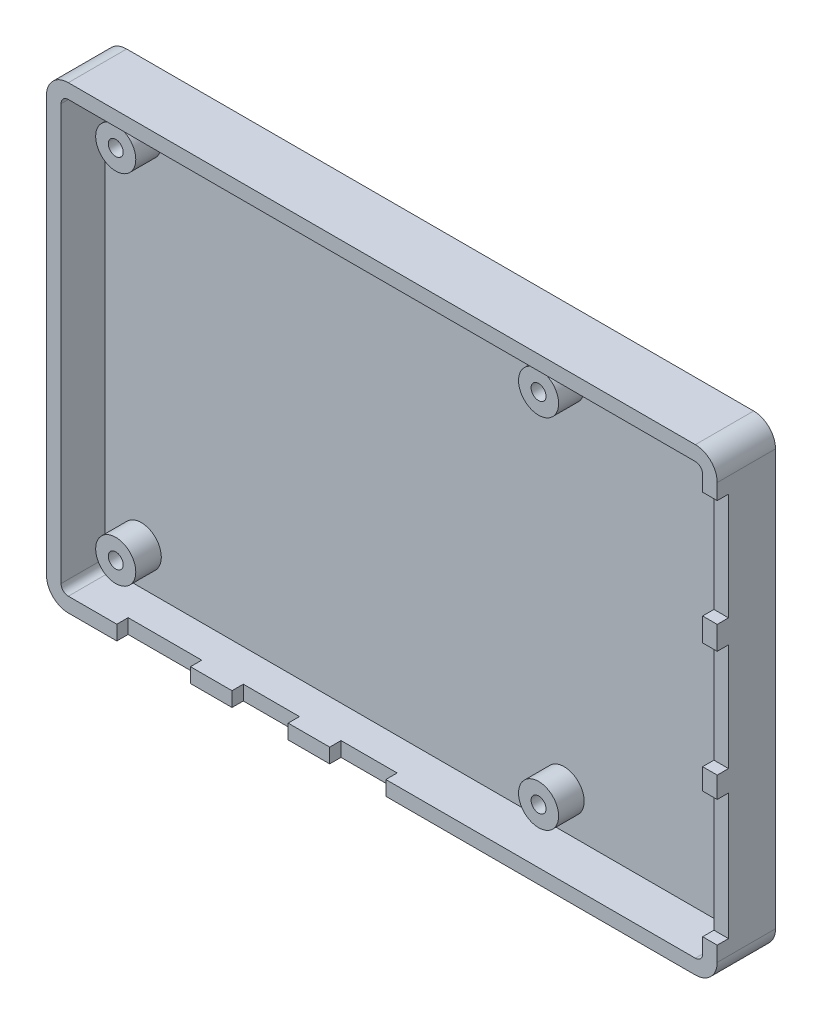
SolidWorks part; units mm, degrees
ref_plane "前视基准面" through (0, 0, 0) normal (0, 0, 1) x (1, 0, 0)
ref_plane "上视基准面" through (0, 0, 0) normal (0, 1, 0) x (1, 0, 0)
ref_plane "右视基准面" through (0, 0, 0) normal (1, 0, 0) x (0, 0, -1)
other "Configuration Table"
sketch "CaseEnvelope" plane through (0, 0, 0) normal (0, 0, 1) x (1, 0, 0)
  line L1 (-46, -31.5) -> (46, -31.5)
  line L2 (-46, -31.5) -> (-46, 31.5)
  line L3 (-46, 31.5) -> (46, 31.5)
  line L4 (46, -31.5) -> (46, 31.5)
  line L5 (-46, -31.5) -> (46, 31.5) construction
  line L6 (-46, 31.5) -> (46, -31.5) construction
  point P0 (0, 0)
  dimension "Length" = 92
  dimension "Width" = 63
extrude "Bottom_Envelope" add sketch "CaseEnvelope" along normal blind 8
fillet "Outside_R3" radius 3 4 edges at (46, 31.5, 4) (46, -31.5, 4) (-46, 31.5, 4) (-46, -31.5, 4)
shell "抽壳1" thickness 2
sketch "SidePort_Profile_1" plane through (0, 0, 0) normal (0, 0, 1) x (1, 0, 0)
  line L0 (-36.35, -40) -> (-26.25, -40)
  line L1 (-26.25, -40) -> (-26.25, -27)
  line L2 (-26.25, -27) -> (-36.35, -27)
  line L3 (-36.35, -27) -> (-36.35, -40)
extrude "SidePort_Clearance_1" cut sketch "SidePort_Profile_1" along normal blind 4.5 from offset 6.45
sketch "SidePort_Profile_2" plane through (0, 0, 0) normal (0, 0, 1) x (1, 0, 0)
  line L0 (-20.55, -40) -> (-12.85, -40)
  line L1 (-12.85, -40) -> (-12.85, -27)
  line L2 (-12.85, -27) -> (-20.55, -27)
  line L3 (-20.55, -27) -> (-20.55, -40)
extrude "SidePort_Clearance_2" cut sketch "SidePort_Profile_2" along normal blind 4.7 from offset 6.45
sketch "SidePort_Profile_3" plane through (0, 0, 0) normal (0, 0, 1) x (1, 0, 0)
  line L0 (-7.15, -40) -> (0.55, -40)
  line L1 (0.55, -40) -> (0.55, -27)
  line L2 (0.55, -27) -> (-7.15, -27)
  line L3 (-7.15, -27) -> (-7.15, -40)
extrude "SidePort_Clearance_3" cut sketch "SidePort_Profile_3" along normal blind 4.7 from offset 6.45
sketch "EndPort_Profile_1" plane through (0, 0, 0) normal (0, 0, 1) x (1, 0, 0)
  line L0 (42, -26.45) -> (53, -26.45)
  line L1 (53, -26.45) -> (53, -9.15)
  line L2 (53, -9.15) -> (42, -9.15)
  line L3 (42, -9.15) -> (42, -26.45)
extrude "EndPort_Clearance_1" cut sketch "EndPort_Profile_1" along normal blind 14.6 from offset 6.45
sketch "EndPort_Profile_2" plane through (0, 0, 0) normal (0, 0, 1) x (1, 0, 0)
  line L0 (42, -6.25) -> (53, -6.25)
  line L1 (53, -6.25) -> (53, 8.45)
  line L2 (53, 8.45) -> (42, 8.45)
  line L3 (42, 8.45) -> (42, -6.25)
extrude "EndPort_Clearance_2" cut sketch "EndPort_Profile_2" along normal blind 16.3 from offset 6.45
sketch "EndPort_Profile_3" plane through (0, 0, 0) normal (0, 0, 1) x (1, 0, 0)
  line L0 (42, 11.65) -> (53, 11.65)
  line L1 (53, 11.65) -> (53, 26.35)
  line L2 (53, 26.35) -> (42, 26.35)
  line L3 (42, 26.35) -> (42, 11.65)
extrude "EndPort_Clearance_3" cut sketch "EndPort_Profile_3" along normal blind 16.3 from offset 6.45
sketch "Standoff_Rings" plane through (0, 0, 0) normal (0, 0, 1) x (1, 0, 0)
  circle A0 centre (-39, -24.5) radius 2.75
  circle A1 centre (-39, 24.5) radius 2.75
  circle A2 centre (19, -24.5) radius 2.75
  circle A3 centre (19, 24.5) radius 2.75
  circle A4 centre (-39, -24.5) radius 1.025
  circle A5 centre (-39, 24.5) radius 1.025
  circle A6 centre (19, -24.5) radius 1.025
  circle A7 centre (19, 24.5) radius 1.025
extrude "Four_M2p5_Standoffs_2p05_Pilot" add sketch "Standoff_Rings" along normal blind 3.5 from offset 2
